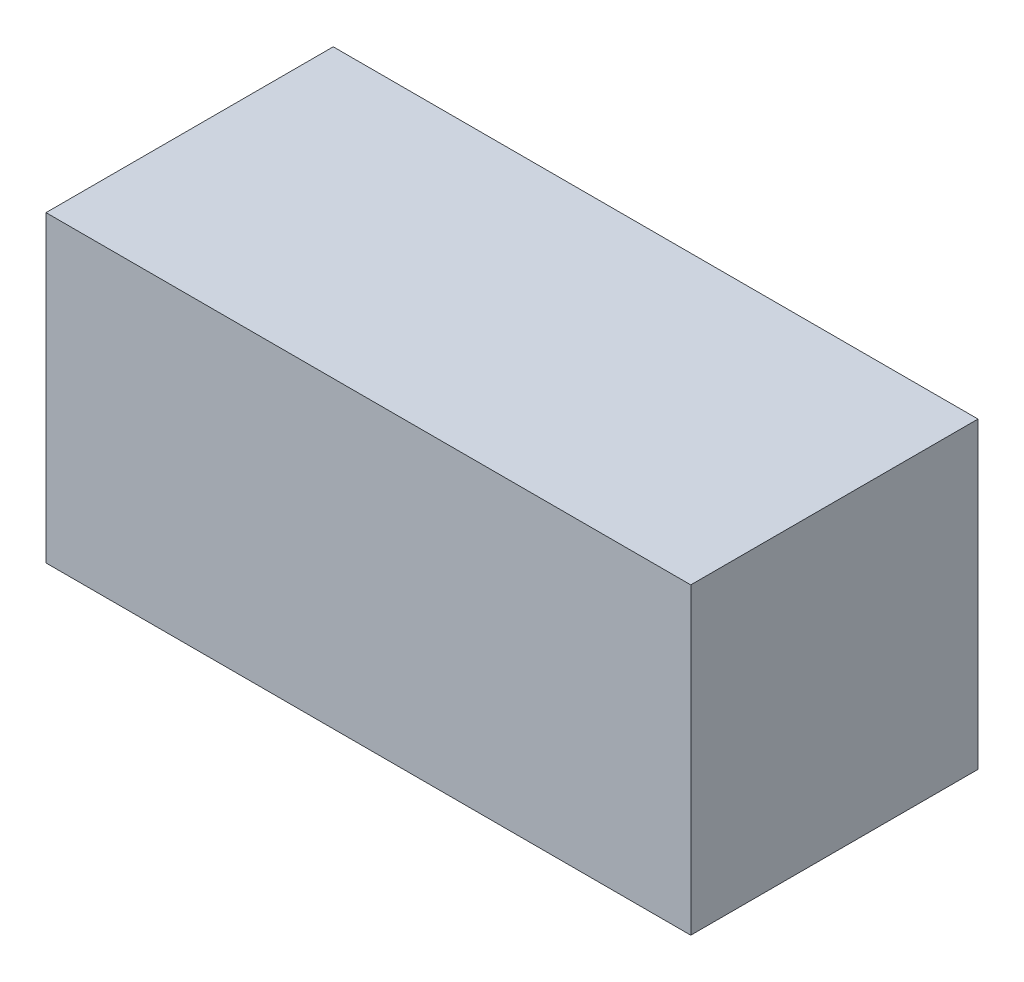
SolidWorks part; units mm, degrees
material "ABS"
ref_plane "X-Y Datum" through (0, 0, 0) normal (0, 0, 1) x (1, 0, 0)
ref_plane "X-Z Datum" through (0, 0, 0) normal (0, 1, 0) x (1, 0, 0)
ref_plane "Y-Z Datum" through (0, 0, 0) normal (1, 0, 0) x (0, 0, -1)
sketch "Sketch1" plane through (0, 0, 0) normal (0, 0, 1) x (1, 0, 0)
  line L1 (-80.9625, 38.1) -> (80.9625, 38.1)
  line L2 (-80.9625, 38.1) -> (-80.9625, -38.1)
  line L3 (-80.9625, -38.1) -> (80.9625, -38.1)
  line L4 (80.9625, 38.1) -> (80.9625, -38.1)
  line L5 (-80.9625, 38.1) -> (80.9625, -38.1) construction
  line L6 (-80.9625, -38.1) -> (80.9625, 38.1) construction
  point P0 (0, 0)
  dimension "D1" = 161.925
  dimension "D2" = 76.2
extrude "Boss-Extrude1" add sketch "Sketch1" along normal blind 72.136
